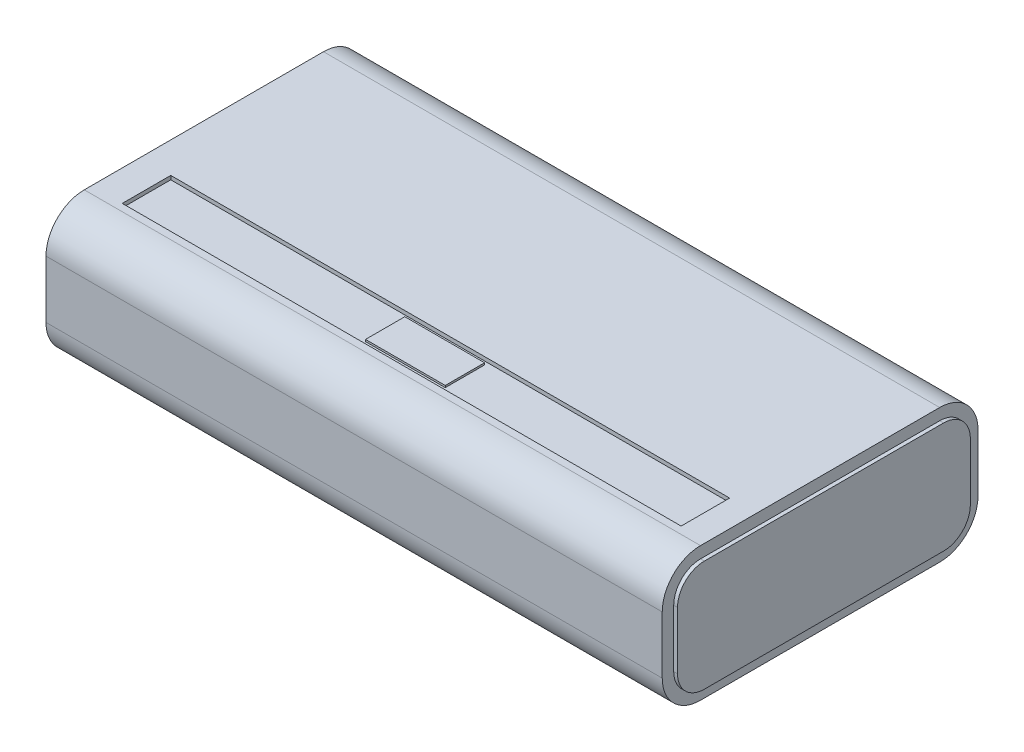
SolidWorks part; units mm, degrees
ref_plane "Front Plane" through (0, 0, 0) normal (0, 0, 1) x (1, 0, 0)
ref_plane "Top Plane" through (0, 0, 0) normal (0, 1, 0) x (1, 0, 0)
ref_plane "Right Plane" through (0, 0, 0) normal (1, 0, 0) x (0, 0, -1)
sketch "Sketch1" plane through (0, 0, 0) normal (0, 1, 0) x (1, 0, 0)
  line L1 (80.5, -41.25) -> (-80.5, -41.25)
  line L2 (80.5, -41.25) -> (80.5, 41.25)
  line L3 (80.5, 41.25) -> (-80.5, 41.25)
  line L4 (-80.5, -41.25) -> (-80.5, 41.25)
  line L5 (80.5, -41.25) -> (-80.5, 41.25) construction
  line L6 (80.5, 41.25) -> (-80.5, -41.25) construction
  point P0 (0, 0)
  dimension "D1" = 161
  dimension "D2" = 82.5
extrude "Boss-Extrude1" add sketch "Sketch1" along normal blind 35
fillet "Fillet1" radius 10 4 edges at (0, 35, -41.25) (0, 0, -41.25) (0, 0, 41.25) (0, 35, 41.25)
sketch "Sketch2" plane through (80.5, 0, 0) normal (1, 0, 0) x (0, 0, -1)
  line L8 (38.25, 10) -> (38.25, 25)
  line L9 (31.25, 32) -> (-31.25, 32)
  line L10 (-38.25, 25) -> (-38.25, 10)
  line L11 (-31.25, 3) -> (31.25, 3)
  line L12 (38.25, 10) -> (38.25, 25)
  line L13 (31.25, 32) -> (-31.25, 32)
  line L14 (-38.25, 25) -> (-38.25, 10)
  line L15 (-31.25, 3) -> (31.25, 3)
  arc A8 (38.25, 25) -> (31.25, 32) centre (31.25, 25) ccw
  arc A9 (-31.25, 32) -> (-38.25, 25) centre (-31.25, 25) ccw
  arc A10 (-38.25, 10) -> (-31.25, 3) centre (-31.25, 10) ccw
  arc A11 (31.25, 3) -> (38.25, 10) centre (31.25, 10) ccw
  arc A12 (38.25, 25) -> (31.25, 32) centre (31.25, 25) ccw
  arc A13 (-31.25, 32) -> (-38.25, 25) centre (-31.25, 25) ccw
  arc A14 (-38.25, 10) -> (-31.25, 3) centre (-31.25, 10) ccw
  arc A15 (31.25, 3) -> (38.25, 10) centre (31.25, 10) ccw
  dimension "D1" = 3
extrude "Boss-Extrude2" add sketch "Sketch2" along normal blind 1
sketch "Sketch3" plane through (-80.5, 0, 0) normal (-1, 0, 0) x (0, 0, 1)
  line L8 (31.25, 32) -> (-31.25, 32)
  line L9 (-38.25, 25) -> (-38.25, 10)
  line L10 (-31.25, 3) -> (31.25, 3)
  line L11 (38.25, 10) -> (38.25, 25)
  line L12 (31.25, 32) -> (-31.25, 32)
  line L13 (-38.25, 25) -> (-38.25, 10)
  line L14 (-31.25, 3) -> (31.25, 3)
  line L15 (38.25, 10) -> (38.25, 25)
  arc A8 (-31.25, 32) -> (-38.25, 25) centre (-31.25, 25) ccw
  arc A9 (-38.25, 10) -> (-31.25, 3) centre (-31.25, 10) ccw
  arc A10 (31.25, 3) -> (38.25, 10) centre (31.25, 10) ccw
  arc A11 (38.25, 25) -> (31.25, 32) centre (31.25, 25) ccw
  arc A12 (-31.25, 32) -> (-38.25, 25) centre (-31.25, 25) ccw
  arc A13 (-38.25, 10) -> (-31.25, 3) centre (-31.25, 10) ccw
  arc A14 (31.25, 3) -> (38.25, 10) centre (31.25, 10) ccw
  arc A15 (38.25, 25) -> (31.25, 32) centre (31.25, 25) ccw
  dimension "D1" = 3
extrude "Boss-Extrude3" add sketch "Sketch3" along normal blind 1
sketch "Sketch4" plane through (0, 35, 0) normal (0, 1, 0) x (1, 0, 0)
  line L1 (73.5495, -29.358) -> (-72.4679, -29.358)
  line L2 (73.5495, -29.358) -> (73.5495, -16.6877)
  line L3 (73.5495, -16.6877) -> (-72.4679, -16.6877)
  line L4 (-72.4679, -29.358) -> (-72.4679, -16.6877)
  line L5 (73.5495, -29.358) -> (-72.4679, -16.6877) construction
  line L6 (73.5495, -16.6877) -> (-72.4679, -29.358) construction
  point P0 (0.5408, -23.0229)
extrude "Cut-Extrude1" cut sketch "Sketch4" against normal blind 1
sketch "Sketch6" plane through (0, 34, 0) normal (0, 1, 0) x (1, 0, 0)
  line L1 (10.4171, -27.8556) -> (-10.4171, -27.8556)
  line L2 (10.4171, -27.8556) -> (10.4171, -17.5891)
  line L3 (10.4171, -17.5891) -> (-10.4171, -17.5891)
  line L4 (-10.4171, -27.8556) -> (-10.4171, -17.5891)
  line L5 (10.4171, -27.8556) -> (-10.4171, -17.5891) construction
  line L6 (10.4171, -17.5891) -> (-10.4171, -27.8556) construction
  point P0 (0, -22.7224)
extrude "Boss-Extrude5" add sketch "Sketch6" along normal blind 0.5
sketch "Sketch7" plane through (-81.5, 0, 0) normal (-1, 0, 0) x (0, 0, 1)
  circle A0 centre (0, 17.3045) radius 8.6059
extrude "Boss-Extrude6" add sketch "Sketch7" along normal blind 0.5
sketch "Sketch8" plane through (0, 34.5, 0) normal (0, 1, 0) x (1, 0, 0)
  line L0 (13.0878, 2.1856) -> (105.0878, 2.1856) construction
sketch "Sketch9" plane through (0, 35, 0) normal (0, 1, 0) x (1, 0, 0)
  line L0 (-9.9662, 27.3869) -> (250.7005, 27.3869) construction
